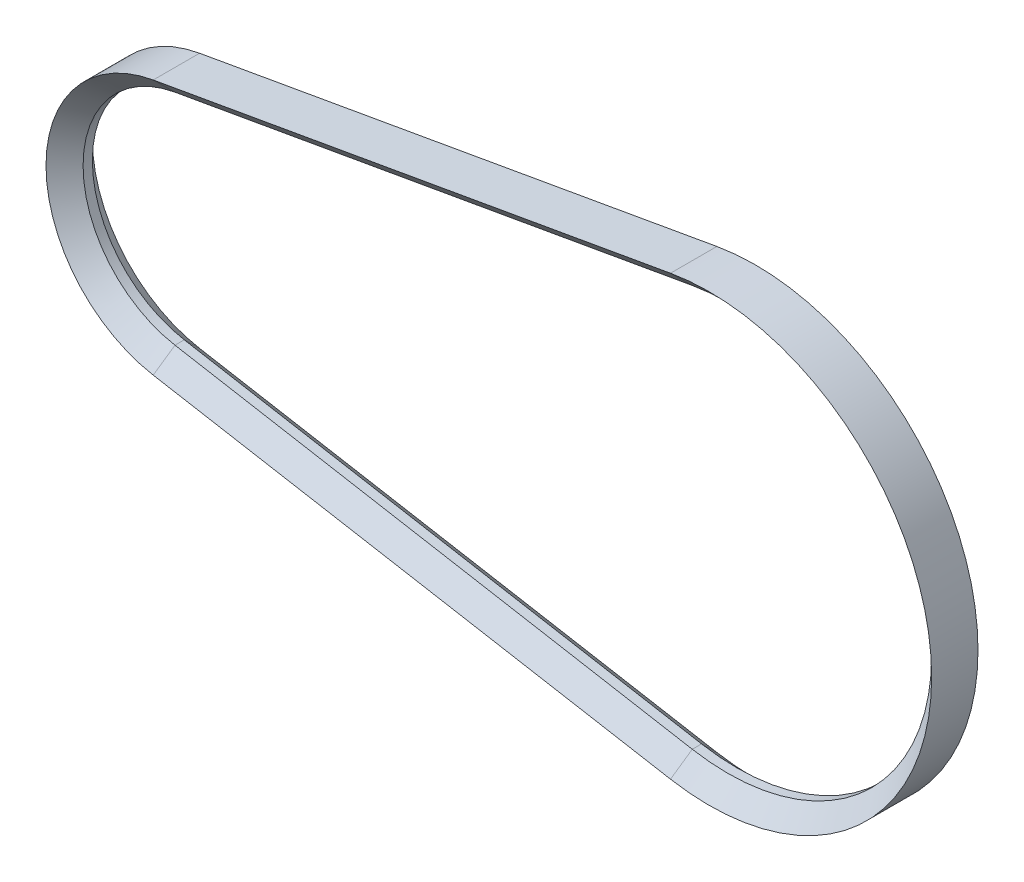
SolidWorks part; units mm, degrees
ref_plane "Face" through (0, 0, 0) normal (0, 0, 1) x (1, 0, 0)
ref_plane "Dessus" through (0, 0, 0) normal (0, 1, 0) x (1, 0, 0)
ref_plane "Droite" through (0, 0, 0) normal (1, 0, 0) x (0, 0, -1)
sketch "Esquisse1" plane through (0, 0, 0) normal (0, 0, 1) x (1, 0, 0)
  line L0 (26.8583, 10.8326) -> (-1.0428, 5.9087)
  line L1 (28.77, 0) -> (0, 0) construction
  line L2 (26.8583, -10.8326) -> (-1.0428, -5.9087)
  arc A0 (-1.0428, 5.9087) -> (-1.0428, -5.9087) centre (0, 0) ccw
  arc A1 (26.8583, -10.8326) -> (26.8583, 10.8326) centre (28.77, 0) ccw
  dimension "D2" = 6
  dimension "D3" = 11
  dimension "D1" = 28.77
sketch "Esquisse2" plane through (0, 0, 0) normal (0, 1, 0) x (1, 0, 0)
  line L0 (0, 0) -> (-35.5281, 0) construction
  line L1 (-7, -1.25) -> (-7, 1.25)
  line L2 (-7, 1.25) -> (-6, 0.25)
  line L3 (-7, -1.25) -> (-6, -0.25)
  line L4 (-6, 0.25) -> (-6, -0.25)
  point P6 (-7, 0)
  point P9 (-6, 0)
  dimension "D1" = 45
  dimension "D2" = 2.5
  dimension "D3" = 1
  dimension "D4" = 6
sweep "Balayage1" add profiles "Esquisse2" path "Esquisse1"
